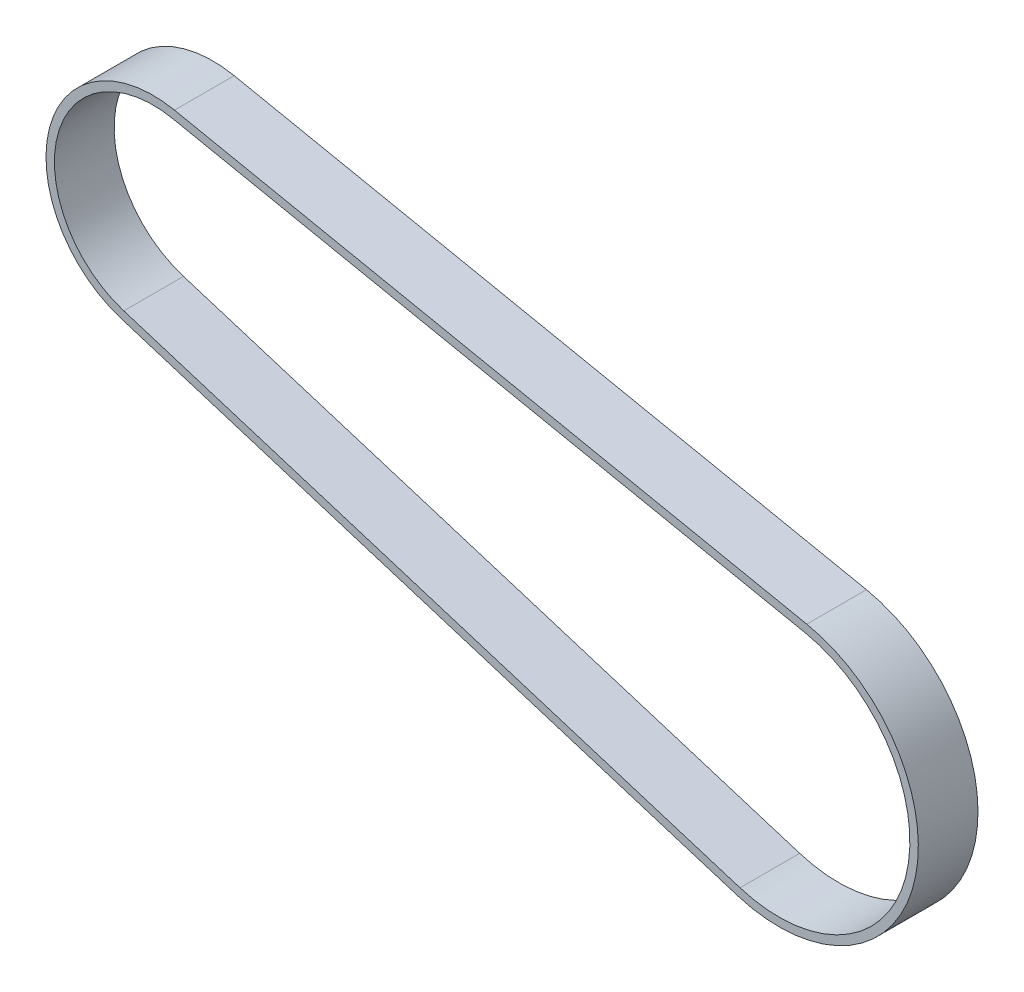
SolidWorks part; units mm, degrees
material "POLYURETHANE (11671)"
ref_plane "Front Plane" through (0, 0, 0) normal (0, 0, 1) x (1, 0, 0)
ref_plane "Top Plane" through (0, 0, 0) normal (0, 1, 0) x (1, 0, 0)
ref_plane "Right Plane" through (0, 0, 0) normal (1, 0, 0) x (0, 0, -1)
sketch "Sketch2" plane through (0, 0, 0) normal (0, 0, 1) x (1, 0, 0)
  line L0 (0, 0) -> (1, 0) construction
  line L1 (0, 0) -> (0, 1) construction
  line L2 (16.4853, 12.701) -> (111.8082, -6.7492)
  line L3 (101.9974, -44.9603) -> (9.0949, -16.0831)
  arc A0 (9.0949, -16.0831) -> (16.4853, 12.701) centre (13.5109, -1.8761) cw
  arc A1 (111.8082, -6.7492) -> (101.9974, -44.9603) centre (107.8597, -26.1004) cw
extrude "Extrude-Thin1" add sketch "Sketch2" along normal blind 9 thin thin type one direction wall 1.27
